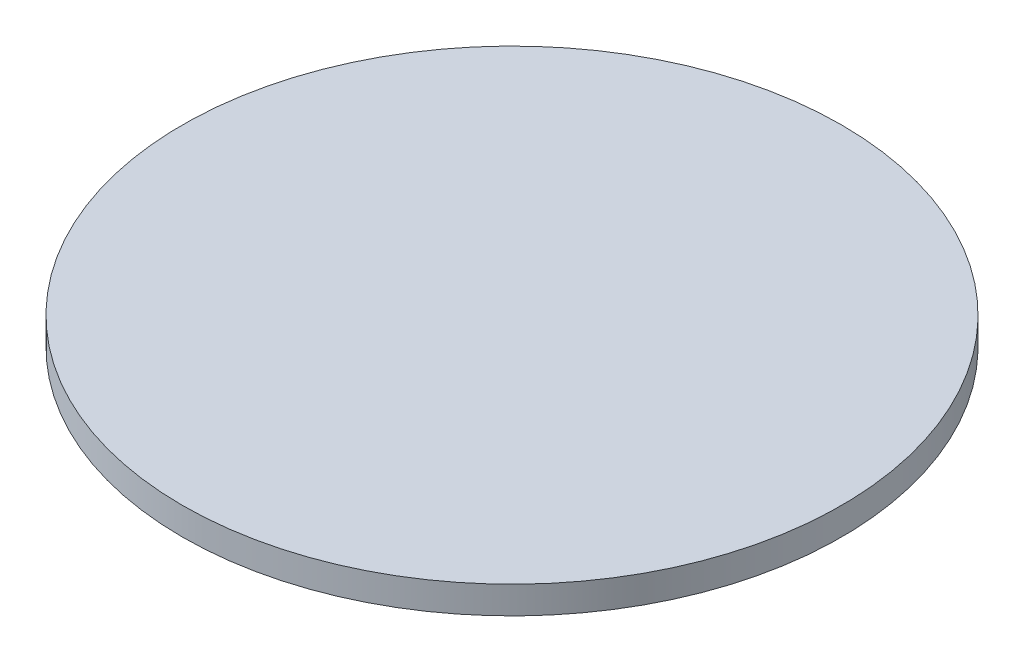
SolidWorks part; units mm, degrees
ref_plane "Front Plane" through (0, 0, 0) normal (0, 0, 1) x (1, 0, 0)
ref_plane "Top Plane" through (0, 0, 0) normal (0, 1, 0) x (1, 0, 0)
ref_plane "Right Plane" through (0, 0, 0) normal (1, 0, 0) x (0, 0, -1)
sketch "Sketch1" plane through (0, 0, 0) normal (0, 1, 0) x (1, 0, 0)
  circle A0 centre (0, 0) radius 38.1
  dimension "D1" = 76.2
extrude "Boss-Extrude1" add sketch "Sketch1" along normal blind 3.175
equation "\"airframeInnerDiameter\"=3"
equation "\"D1@Sketch1\"=\"airframeInnerDiameter\""
